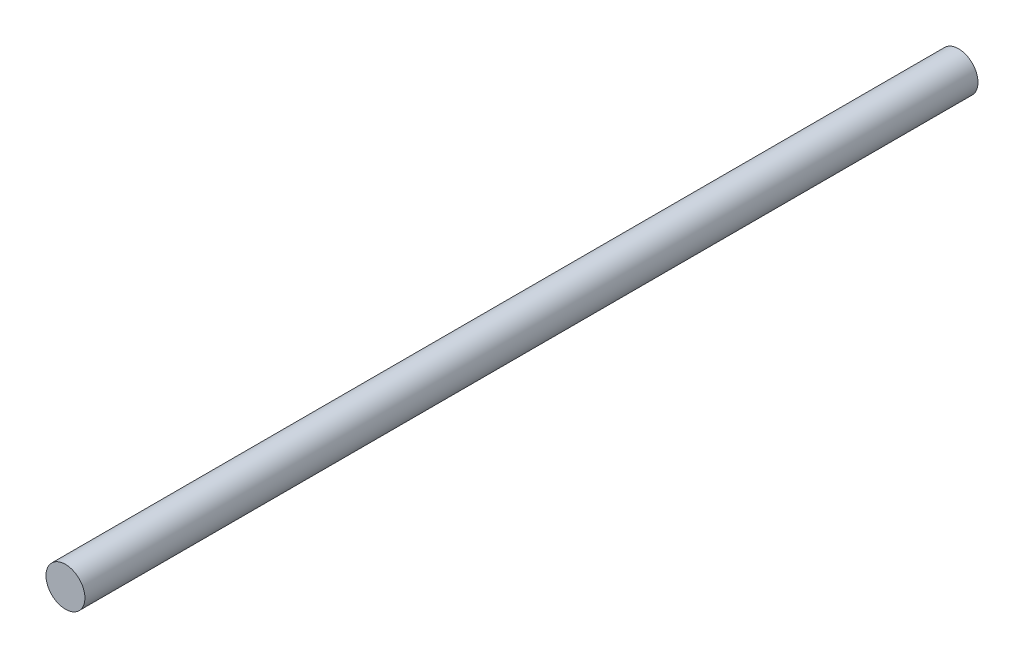
SolidWorks part; units mm, degrees
ref_plane "Front Plane" through (0, 0, 0) normal (0, 0, 1) x (1, 0, 0)
ref_plane "Top Plane" through (0, 0, 0) normal (0, 1, 0) x (1, 0, 0)
ref_plane "Right Plane" through (0, 0, 0) normal (1, 0, 0) x (0, 0, -1)
sketch "Sketch2" plane through (0, 0, 0) normal (0, 0, 1) x (1, 0, 0)
  circle A0 centre (0, 0) radius 10.9
  dimension "D1" = 21.8
extrude "Boss-Extrude1" add sketch "Sketch2" against normal blind 500
